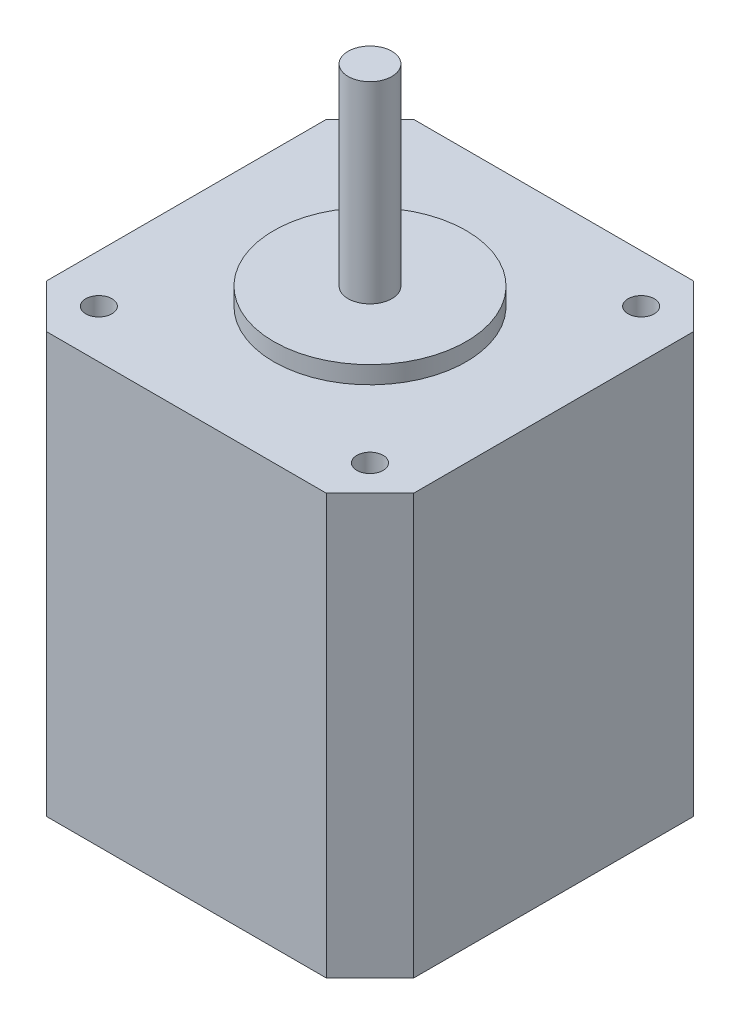
SolidWorks part; units mm, degrees
ref_plane "Front Plane" through (0, 0, 0) normal (0, 0, 1) x (1, 0, 0)
ref_plane "Top Plane" through (0, 0, 0) normal (0, 1, 0) x (1, 0, 0)
ref_plane "Right Plane" through (0, 0, 0) normal (1, 0, 0) x (0, 0, -1)
sketch "Sketch1" plane through (0, 0, 0) normal (0, 1, 0) x (1, 0, 0)
  line L1 (0, 0) -> (42, 0)
  line L2 (0, 0) -> (0, 42)
  line L3 (0, 42) -> (42, 42)
  line L4 (42, 0) -> (42, 42)
  dimension "D1" = 42
  dimension "D2" = 42
extrude "Boss-Extrude1" add sketch "Sketch1" along normal blind 48
chamfer "Chamfer1" distance 5 angle 45 4 edges at (0, 24, -42) (42, 24, -42) (0, 24, 0) (42, 24, 0)
sketch "Sketch2" plane through (0, 48, 0) normal (0, 1, 0) x (1, 0, 0)
  line L1 (42, 5) -> (42, 37) construction
  line L2 (37, 42) -> (5, 42) construction
  circle A0 centre (5.5, 36.5) radius 1.5
  circle A1 centre (36.5, 36.5) radius 1.5
  circle A2 centre (5.5, 5.5) radius 1.5
  circle A3 centre (36.5, 5.5) radius 1.5
  point P10 (-17.6981, 45.9076)
  point P11 (-24.4872, 44.4649)
  dimension "D1" = 3
  dimension "D2" = 3
  dimension "D3" = 3
  dimension "D4" = 3
  dimension "D5" = 31
  dimension "D6" = 31
  dimension "D7" = 0
  dimension "D8" = 0
  dimension "D9" = 31
  dimension "D10" = 31
  dimension "D11" = 5.5
  dimension "D12" = 5.5
extrude "Cut-Extrude1" cut sketch "Sketch2" against normal blind 4.5
sketch "Sketch3" plane through (0, 48, 0) normal (0, 1, 0) x (1, 0, 0)
  line L0 (37, 42) -> (5, 42) construction
  line L1 (42, 5) -> (42, 37) construction
  circle A0 centre (21, 21) radius 11
  dimension "D1" = 22
  dimension "D2" = 21
  dimension "D3" = 21
extrude "Boss-Extrude2" add sketch "Sketch3" along normal blind 2
sketch "Sketch4" plane through (0, 50, 0) normal (0, 1, 0) x (1, 0, 0)
  circle A0 centre (21, 21) radius 2.5
  dimension "D1" = 5
extrude "Boss-Extrude3" add sketch "Sketch4" along normal blind 22
